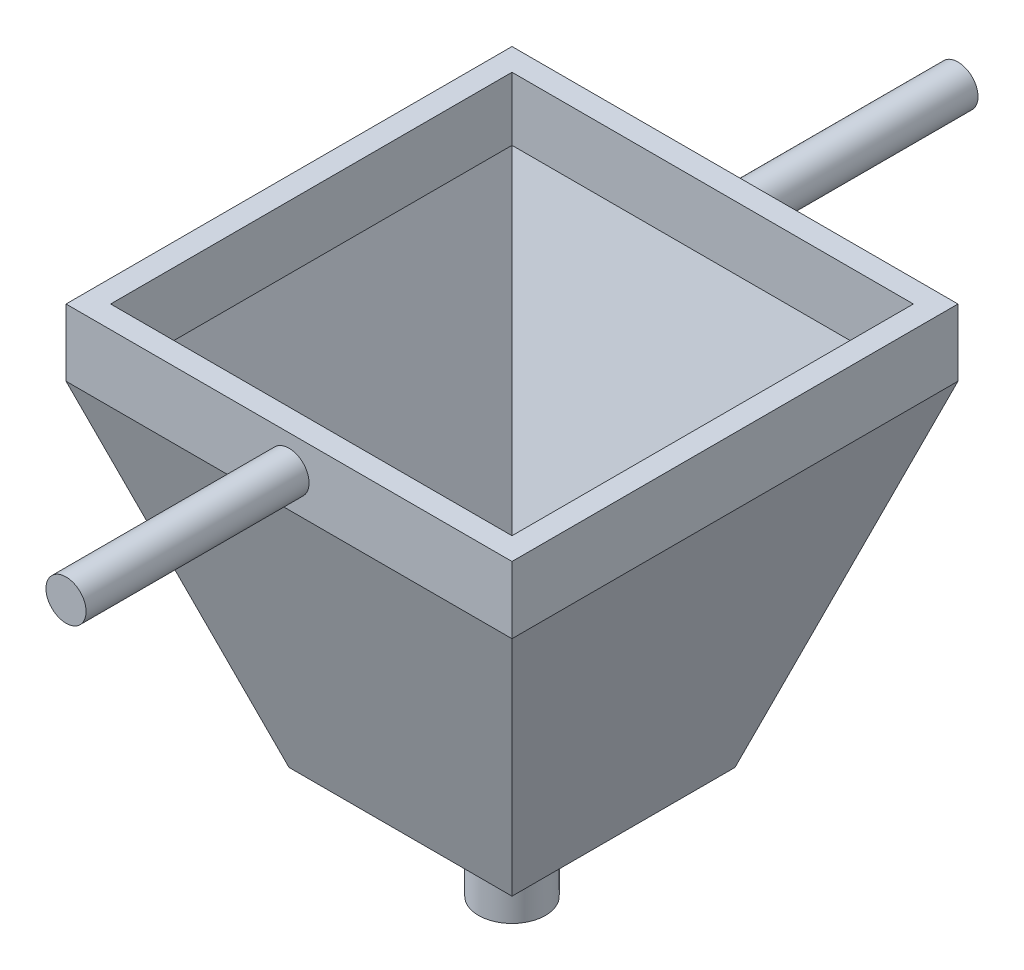
SolidWorks part; units mm, degrees
ref_plane "Alzado" through (0, 0, 0) normal (0, 0, 1) x (1, 0, 0)
ref_plane "Planta" through (0, 0, 0) normal (0, 1, 0) x (1, 0, 0)
ref_plane "Vista lateral" through (0, 0, 0) normal (1, 0, 0) x (0, 0, -1)
sketch "Croquis1" plane through (0, 0, 0) normal (0, 1, 0) x (1, 0, 0)
  line L1 (-5, -5) -> (5, -5)
  line L2 (-5, -5) -> (-5, 5)
  line L3 (-5, 5) -> (5, 5)
  line L4 (5, -5) -> (5, 5)
  line L5 (-5, -5) -> (5, 5) construction
  line L6 (-5, 5) -> (5, -5) construction
  point P0 (0, 0)
  dimension "D1" = 10
  dimension "D2" = 10
ref_plane "Plano1" through (0, 15, 0) normal (0, 1, 0) x (1, 0, 0)
sketch "Croquis2" plane through (0, 15, 0) normal (0, 1, 0) x (1, 0, 0)
  line L1 (-10, -10) -> (10, -10)
  line L2 (-10, -10) -> (-10, 10)
  line L3 (-10, 10) -> (10, 10)
  line L4 (10, -10) -> (10, 10)
  line L5 (-10, -10) -> (10, 10) construction
  line L6 (-10, 10) -> (10, -10) construction
  point P0 (0, 0)
  dimension "D1" = 20
  dimension "D2" = 20
loft "Recubrir1" add profiles "Croquis2", "Croquis1"
sketch "Croquis3" plane through (0, 15, 0) normal (0, 1, 0) x (1, 0, 0)
  line L1 (10, -10) -> (-10, -10)
  line L2 (10, -10) -> (10, 10)
  line L3 (10, 10) -> (-10, 10)
  line L4 (-10, -10) -> (-10, 10)
  line L5 (10, -10) -> (-10, 10) construction
  line L6 (10, 10) -> (-10, -10) construction
  point P0 (0, 0)
extrude "Saliente-Extruir1" add sketch "Croquis3" along normal blind 3
shell "Vaciado2" thickness 1
sketch "Croquis4" plane through (0, 0, 0) normal (0, -1, 0) x (-1, 0, 0)
  circle A0 centre (0, 0) radius 1.5
  dimension "D1" = 3
extrude "Cortar-Extruir1" cut sketch "Croquis4" against normal blind 3
sketch "Croquis5" plane through (0, 0, 0) normal (0, -1, 0) x (-1, 0, 0)
  circle A0 centre (0, 0) radius 1.5
extrude "Saliente-Extruir2" add sketch "Croquis5" along normal blind 5 separate body
sketch "Croquis6" plane through (0, -5, 0) normal (0, -1, 0) x (-1, 0, 0)
  circle A0 centre (0, 0) radius 1.3559
extrude "Cortar-Extruir2" cut sketch "Croquis6" against normal blind 15
sketch "Croquis7" plane through (0, 0, 0) normal (1, 0, 0) x (0, 0, -1)
  circle A0 centre (0, -2.4392) radius 1
  dimension "D1" = 2
extrude "Saliente-Extruir4" add sketch "Croquis7" along normal blind 1.5
ref_plane "Plano4" through (1.5, 0, 0) normal (1, 0, 0) x (0, 0, -1)
sketch "Croquis10" plane through (0, 0, 0) normal (0, -1, 0) x (-1, 0, 0)
  circle A0 centre (0, 0) radius 1.4064
extrude "Cortar-Extruir3" cut sketch "Croquis10" against normal blind 1.5 and the other way blind 31.5
ref_plane "Plano5" through (0, 0, -10) normal (0, 0, -1) x (-1, 0, 0)
sketch "Croquis11" plane through (0, 0, -10) normal (0, 0, -1) x (-1, 0, 0)
  circle A0 centre (0, 16.5) radius 0.9
  dimension "D1" = 1.8
extrude "Cortar-Extruir4" cut sketch "Croquis11" against normal blind 0.2 contours A0
ref_plane "Plano8" through (0, 0, 10) normal (0, 0, 1) x (1, 0, 0)
sketch "Croquis12" plane through (0, 0, 10) normal (0, 0, 1) x (1, 0, 0)
  circle A0 centre (0, 16.5) radius 0.9
  dimension "D1" = 1.8
extrude "Cortar-Extruir5" cut sketch "Croquis12" against normal blind 0.2
ref_plane "Plano10" through (0, 0, -10) normal (0, 0, -1) x (-1, 0, 0)
sketch "Croquis15" plane through (0, 0, -10) normal (0, 0, -1) x (-1, 0, 0)
  circle A0 centre (0, 16.5) radius 0.9
extrude "Saliente-Extruir6" add sketch "Croquis15" along normal blind 10 separate body
ref_plane "Plano11" through (0, 0, 10) normal (0, 0, 1) x (1, 0, 0)
sketch "Croquis16" plane through (0, 0, 10) normal (0, 0, 1) x (1, 0, 0)
  circle A0 centre (0, 16.5) radius 0.9
extrude "Saliente-Extruir7" add sketch "Croquis16" along normal blind 10 separate body
